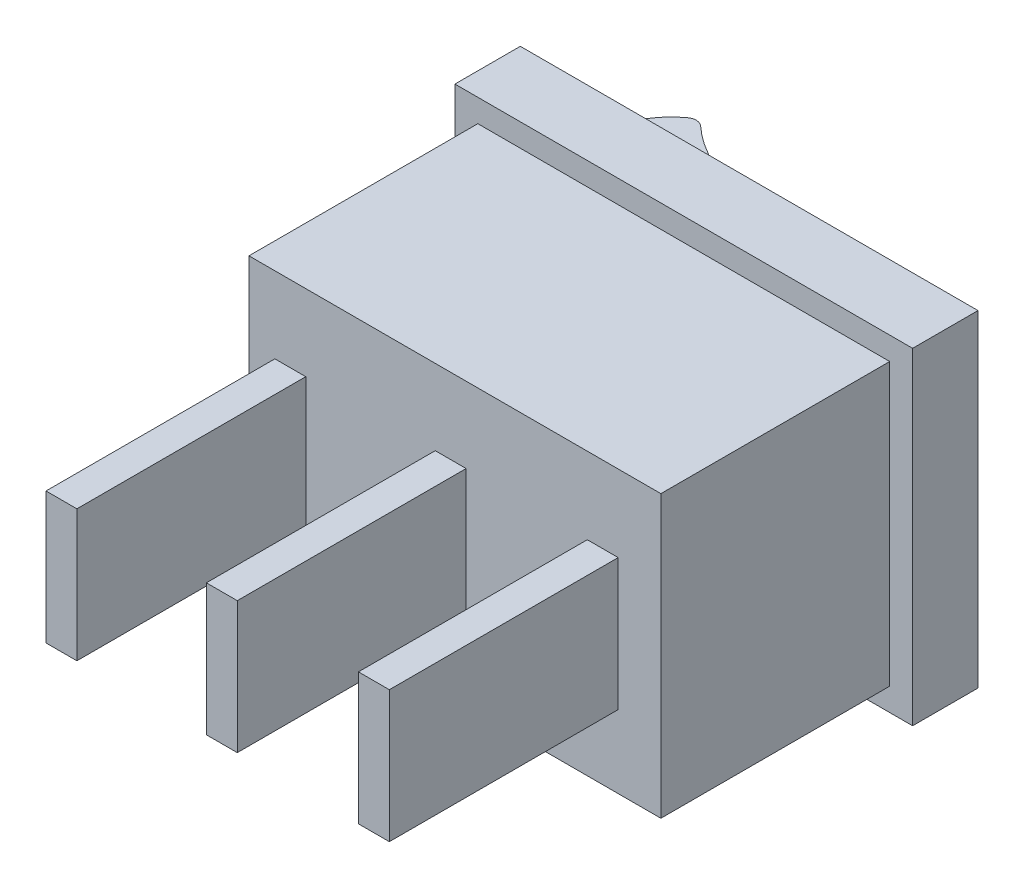
SolidWorks part; units mm, degrees
ref_plane "Alzado" through (0, 0, 0) normal (0, 0, 1) x (1, 0, 0)
ref_plane "Planta" through (0, 0, 0) normal (0, 1, 0) x (1, 0, 0)
ref_plane "Vista lateral" through (0, 0, 0) normal (1, 0, 0) x (0, 0, -1)
sketch "Croquis1" plane through (0, 0, 0) normal (0, 0, 1) x (1, 0, 0)
  line L1 (-10.5, 7.5) -> (10.5, 7.5)
  line L2 (-10.5, 7.5) -> (-10.5, -7.5)
  line L3 (-10.5, -7.5) -> (10.5, -7.5)
  line L4 (10.5, 7.5) -> (10.5, -7.5)
  line L5 (0, -7.5) -> (0, 7.5) construction
  line L6 (-10.5, 0) -> (10.5, 0) construction
  point P0 (0, 0)
  dimension "D1" = 21
  dimension "D2" = 15
extrude "Saliente-Extruir1" add sketch "Croquis1" along normal blind 13.5
sketch "Croquis2" plane through (0, 0, 13.5) normal (0, 0, 1) x (1, 0, 0)
  line L0 (-9.45, 6.45) -> (-9.45, -6.45)
  line L1 (-10.5, 7.5) -> (10.5, 7.5)
  line L2 (-10.5, 7.5) -> (-10.5, -7.5)
  line L3 (-10.5, -7.5) -> (10.5, -7.5)
  line L4 (10.5, 7.5) -> (10.5, -7.5)
  line L5 (-9.45, -6.45) -> (9.45, -6.45)
  line L6 (9.45, 6.45) -> (9.45, -6.45)
  line L7 (-9.45, 6.45) -> (9.45, 6.45)
  dimension "D1" = 18.9
extrude "Cortar-Extruir1" cut sketch "Croquis2" against normal blind 10.5
sketch "Croquis3" plane through (0, 0, 0) normal (0, 1, 0) x (1, 0, 0)
  line L0 (10.5, 0) -> (-10.5, 0) construction
  line L1 (7.0393, 0) -> (-7.9635, 0)
  spline S0 degree 3 poles (7.0393, 0) (4.224, 0.0692) (-0.2147, 0.6668) (-4.5029, 2.2047) (-5.7067, 3.4811) knots 0 0 0 0 0.624058 1 1 1 1
  spline S1 degree 3 poles (-5.7067, 3.4811) (-7.0579, 2.7632) (-7.4885, 1.3074) (-7.9635, 0) knots 0 0 0 0 1 1 1 1
extrude "Saliente-Extruir2" add sketch "Croquis3" along normal mid plane 10.5
fillet "Redondeo1" radius 0.5 1 edges at (-5.7067, 0, -3.4811)
sketch "Croquis4" plane through (0, 0, 13.5) normal (0, 0, 1) x (1, 0, 0)
  line L1 (-8.2618, 2.9502) -> (-6.8437, 2.9502)
  line L2 (-8.2618, 2.9502) -> (-8.2618, -3.0898)
  line L3 (-8.2618, -3.0898) -> (-6.8437, -3.0898)
  line L4 (-6.8437, 2.9502) -> (-6.8437, -3.0898)
  line L5 (-0.903, 2.9801) -> (0.515, 2.9801)
  line L6 (-0.903, 2.9801) -> (-0.903, -3.0599)
  line L7 (-0.903, -3.0599) -> (0.515, -3.0599)
  line L8 (0.515, 2.9801) -> (0.515, -3.0599)
  line L9 (6.0738, 2.9302) -> (7.4918, 2.9302)
  line L10 (6.0738, 2.9302) -> (6.0738, -3.1098)
  line L11 (6.0738, -3.1098) -> (7.4918, -3.1098)
  line L12 (7.4918, 2.9302) -> (7.4918, -3.1098)
  point P12 (0, 2.2584)
  point P13 (7.4985, 1.0546)
  point P14 (7.4918, -3.1098)
  point P15 (0.1636, -3.2336)
  point P16 (0.515, -3.0599)
  point P17 (-6.8437, -3.0898)
extrude "Saliente-Extruir3" add sketch "Croquis4" along normal blind 10.5
